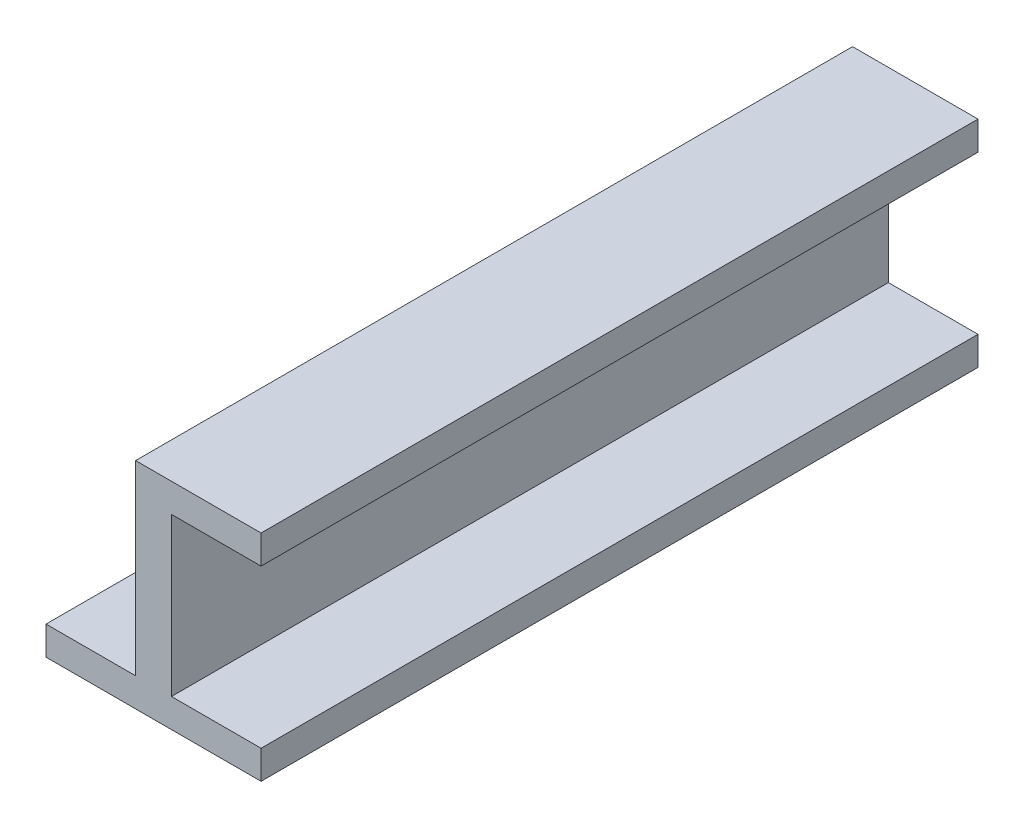
SolidWorks part; units mm, degrees
ref_plane "Спереди" through (0, 0, 0) normal (0, 0, 1) x (1, 0, 0)
ref_plane "Сверху" through (0, 0, 0) normal (0, 1, 0) x (1, 0, 0)
ref_plane "Справа" through (0, 0, 0) normal (1, 0, 0) x (0, 0, -1)
sketch "Эскиз1" plane through (0, 0, 0) normal (0, 0, 1) x (1, 0, 0)
  line L0 (30, -22) -> (0, -22)
  line L1 (0, 22) -> (0, 30)
  line L2 (-5, -30) -> (-5, 30)
  line L3 (-5, 30) -> (5, 30)
  line L4 (5, -30) -> (5, 30)
  line L5 (-5, -30) -> (5, 30) construction
  line L6 (-5, 30) -> (5, -30) construction
  line L7 (-30, -30) -> (-5, -30)
  line L8 (-30, -30) -> (-30, -22)
  line L9 (0, -22) -> (-30, -22)
  line L10 (30, -30) -> (30, -22)
  line L11 (-30, -30) -> (30, -22) construction
  line L12 (-30, -22) -> (30, -30) construction
  line L13 (0, -22) -> (0, -30)
  line L14 (0, 0) -> (5, 0) construction
  line L15 (0, -30) -> (30, -30)
  line L16 (-5, -30) -> (0, -30)
  line L17 (0, 30) -> (30, 30)
  line L18 (30, 30) -> (30, 22)
  line L19 (30, 22) -> (0, 22)
  point P0 (0, 0)
  point P6 (0, -26)
  dimension "D1" = 60
  dimension "D2" = 10
  dimension "D3" = 60
  dimension "D4" = 8
extrude "Бобышка-Вытянуть1" add sketch "Эскиз1" along normal mid plane 200 contours L4 L15 L10 L0 | L13 L15 L4 L0 | L2 L16 L13 L9 | L2 L9 L8 L7 | L4 L19 L1 L3 L2 L9 L0 | L19 L18 L17 L4 | L19 L4 L3 L1
